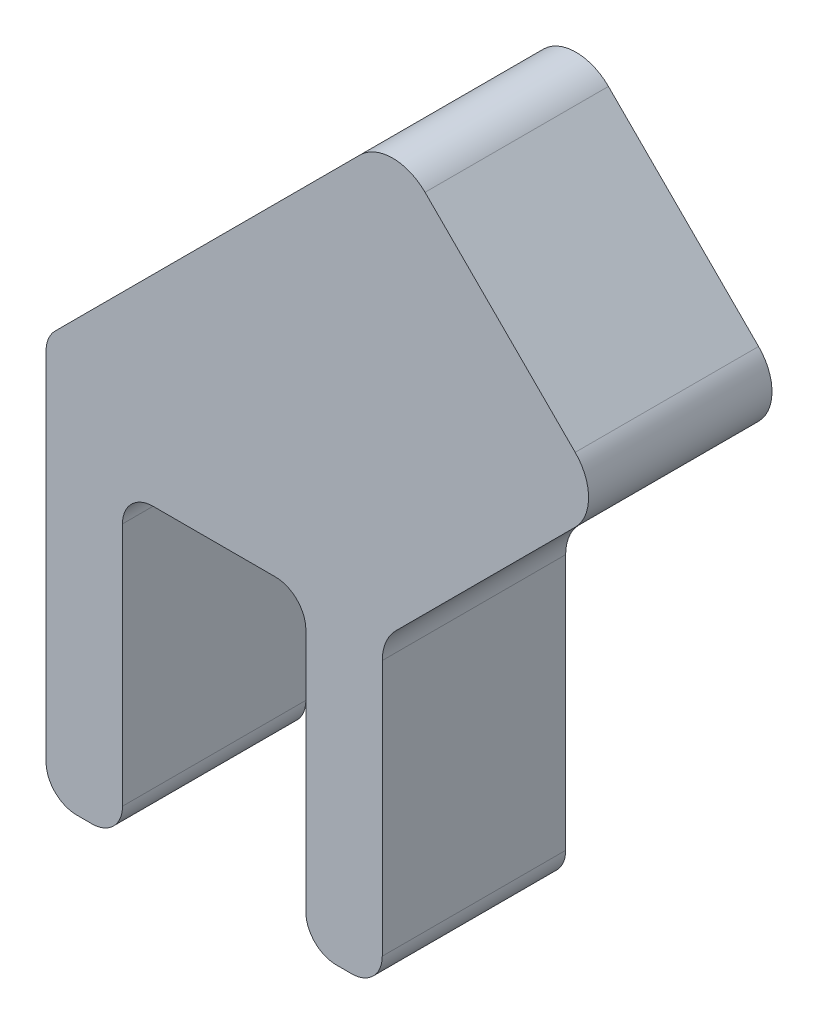
SolidWorks part; units mm, degrees
ref_plane "Спереди" through (0, 0, 0) normal (0, 0, 1) x (1, 0, 0)
ref_plane "Сверху" through (0, 0, 0) normal (0, 1, 0) x (1, 0, 0)
ref_plane "Справа" through (0, 0, 0) normal (1, 0, 0) x (0, 0, -1)
sketch "Эскиз1" plane through (0, 0, 0) normal (0, 0, 1) x (1, 0, 0)
  line L0 (0, 0) -> (76.4746, 0) construction
  line L1 (0, 0) -> (0, 59.0847) construction
  line L2 (0, 0) -> (5, 0)
  line L3 (5, 0) -> (5, 20)
  line L4 (5, 20) -> (17, 20)
  line L5 (17, 20) -> (17, 0)
  line L6 (17, 0) -> (22, 0)
  line L7 (22, 0) -> (22, 18.7574)
  line L8 (0, 0) -> (0, 26.1356)
  line L14 (22.8787, 20.8787) -> (34.6244, 32.6244)
  line L15 (0, 26.1356) -> (20.5566, 46.6922)
  line L16 (34.6244, 36.8671) -> (24.7993, 46.6922)
  arc A0 (24.7993, 46.6922) -> (20.5566, 46.6922) centre (22.678, 44.5709) ccw
  arc A1 (34.6244, 32.6244) -> (34.6244, 36.8671) centre (32.5031, 34.7458) ccw
  arc A2 (22, 18.7574) -> (22.8787, 20.8787) centre (25, 18.7574) cw
  point P19 (22, 20)
  dimension "D6" = 3
  dimension "D1" = 12
  dimension "D2" = 5
  dimension "D3" = 5
  dimension "D4" = 20
  dimension "D5" = 20
extrude "Бобышка-Вытянуть1" add sketch "Эскиз1" along normal blind 12
fillet "Скругление1" radius 2 7 edges at (0, 26.1356, 6) (0, 0, 6) (5, 0, 6) (17, 0, 6) (22, 0, 6) (5, 20, 6) (17, 20, 6)
